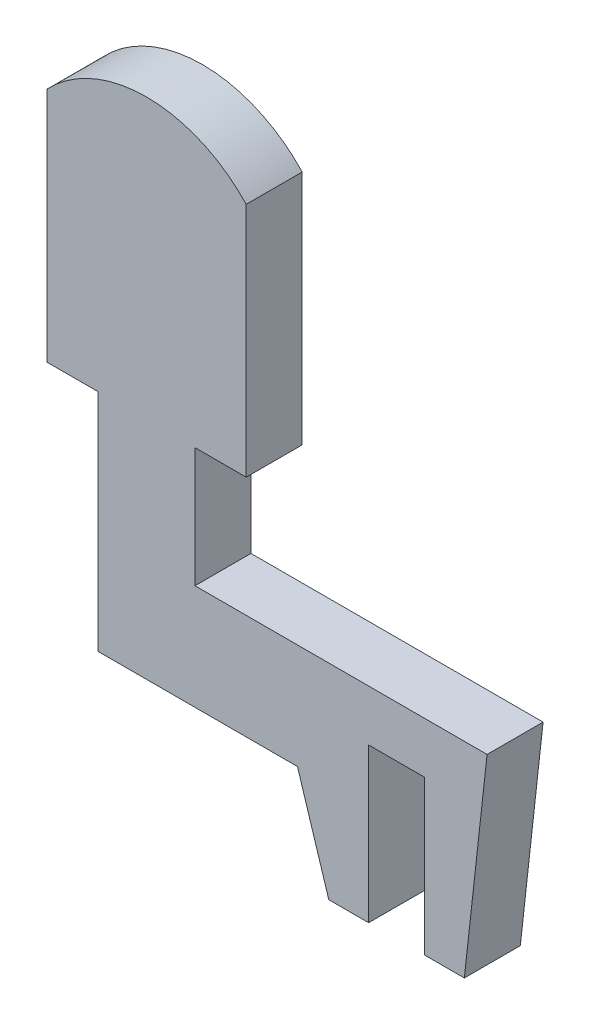
SolidWorks part; units mm, degrees
ref_plane "Front" through (0, 0, 0) normal (0, 0, 1) x (1, 0, 0)
ref_plane "Top" through (0, 0, 0) normal (0, 1, 0) x (1, 0, 0)
ref_plane "Right" through (0, 0, 0) normal (1, 0, 0) x (0, 0, -1)
sketch "Sketch1" plane through (0, 0, 0) normal (0, 0, 1) x (1, 0, 0)
  line L0 (540.4108, 46.3627) -> (540.4108, 39.9534)
  line L1 (540.4108, 39.9534) -> (556.0626, 39.9534)
  line L2 (556.0626, 39.9534) -> (554.8422, 28.9698)
  line L3 (554.8422, 28.9698) -> (552.7079, 28.9698)
  line L4 (552.7079, 28.9698) -> (552.7149, 37.2198)
  line L5 (552.7149, 37.2198) -> (549.7149, 37.2198)
  line L6 (549.7149, 37.2198) -> (549.7149, 28.9698)
  line L7 (549.7149, 28.9698) -> (547.5806, 28.9721)
  line L8 (547.5806, 28.9721) -> (545.9026, 34.3113)
  line L9 (545.9026, 34.3113) -> (535.2241, 34.3113)
  line L10 (535.2241, 34.3113) -> (535.2241, 46.3627)
  line L11 (535.2241, 46.3627) -> (532.4782, 46.3627)
  line L12 (532.4782, 46.3627) -> (532.4782, 46.5153)
  line L13 (532.4782, 46.5153) -> (532.4782, 59.0243)
  line L14 (540.4108, 46.3627) -> (543.1567, 46.3627)
  line L15 (543.1567, 46.3627) -> (543.1567, 59.0243)
  arc A0 (543.1567, 59.0243) -> (532.4782, 59.0243) centre (537.8174, 54.0156) ccw
  dimension "D1" = 3
  dimension "D2" = 8.25
  dimension "D3" = 8.25
extrude "Base-Extrude" add sketch "Sketch1" along normal blind 3
